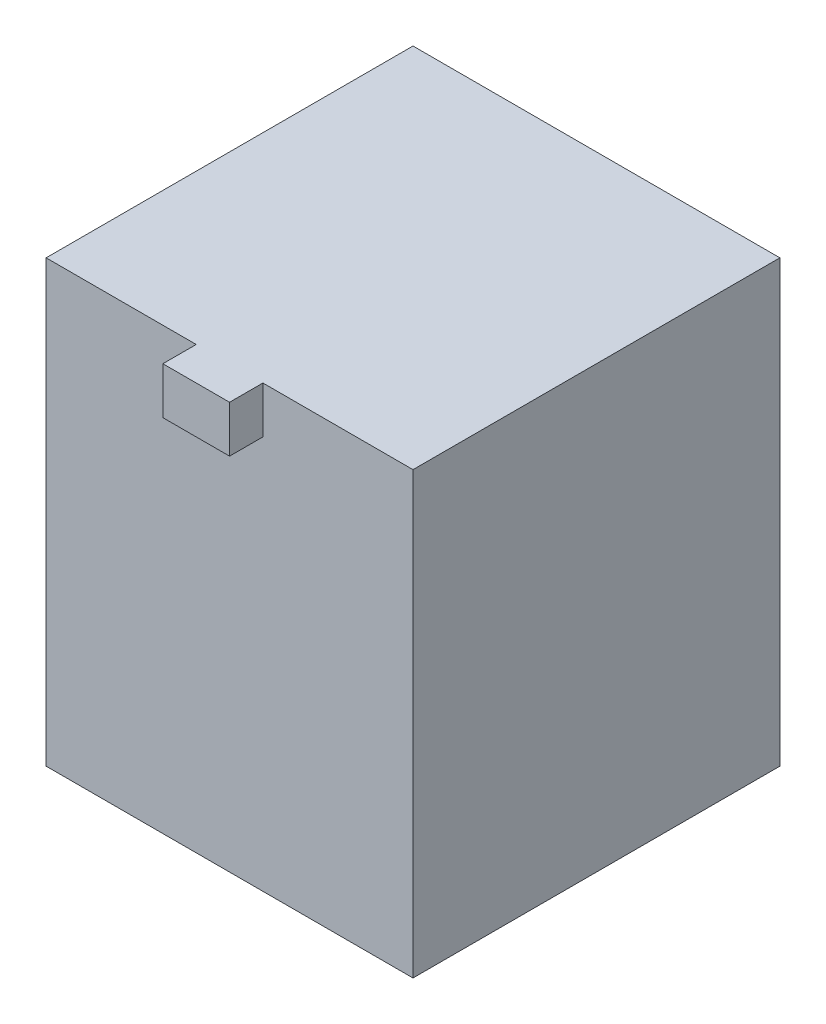
SolidWorks part; units mm, degrees
material "1060 合金"
ref_plane "前视基准面" through (0, 0, 0) normal (0, 0, 1) x (1, 0, 0)
ref_plane "上视基准面" through (0, 0, 0) normal (0, 1, 0) x (1, 0, 0)
ref_plane "右视基准面" through (0, 0, 0) normal (1, 0, 0) x (0, 0, -1)
other "Configuration Table"
sketch "草图1" plane through (0, 0, 0) normal (0, 1, 0) x (1, 0, 0)
  line L1 (-27.5, -27.5) -> (27.5, -27.5)
  line L2 (-27.5, -27.5) -> (-27.5, 27.5)
  line L3 (-27.5, 27.5) -> (27.5, 27.5)
  line L4 (27.5, -27.5) -> (27.5, 27.5)
  line L5 (-27.5, -27.5) -> (27.5, 27.5) construction
  line L6 (-27.5, 27.5) -> (27.5, -27.5) construction
  point P0 (0, 0)
  dimension "D1" = 55
  dimension "D2" = 55
extrude "凸台-拉伸1" add sketch "草图1" along normal blind 66
sketch "草图2" plane through (0, 0, 27.5) normal (0, 0, 1) x (1, 0, 0)
  line L0 (0, 0) -> (0, 68.6632) construction
  line L1 (-5, 66) -> (5, 66)
  line L2 (-27.5, 66) -> (27.5, 66) construction
  line L3 (5, 66) -> (5, 59)
  line L4 (5, 59) -> (-5, 59)
  line L5 (-5, 66) -> (-5, 59)
  point P10 (0, 59)
  point P11 (0, 66)
  dimension "D1" = 10
  dimension "D2" = 7
extrude "凸台-拉伸2" add sketch "草图2" along normal blind 5
